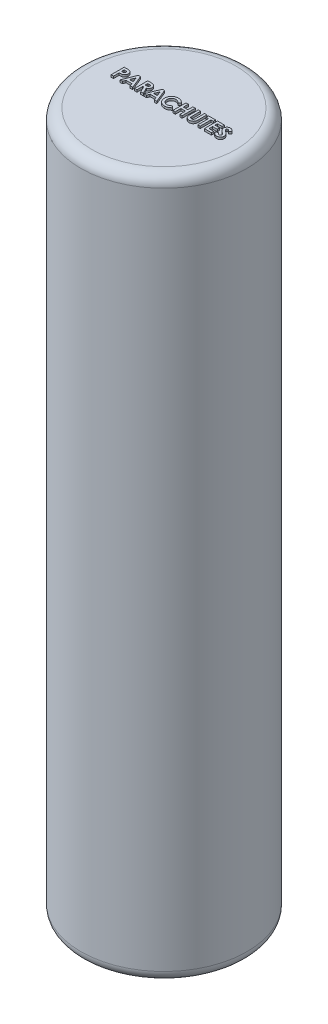
SolidWorks part; units mm, degrees
ref_plane "Front Plane" through (0, 0, 0) normal (0, 0, 1) x (1, 0, 0)
ref_plane "Top Plane" through (0, 0, 0) normal (0, 1, 0) x (1, 0, 0)
ref_plane "Right Plane" through (0, 0, 0) normal (1, 0, 0) x (0, 0, -1)
sketch "Sketch1" plane through (0, 0, 0) normal (0, 1, 0) x (1, 0, 0)
  circle A0 centre (0, 0) radius 48.26
  dimension "D1" = 96.52
extrude "Boss-Extrude1" add sketch "Sketch1" along normal blind 406.4
fillet "Fillet1" radius 6.35 2 edges at (0, 0, 48.26) (0, 406.4, 48.26)
sketch "Sketch2" plane through (0, 406.4, 0) normal (0, 1, 0) x (1, 0, 0)
  line L0 (35.8256, 0) -> (-35.8256, 0) construction
  text T0 "<b>PARACHUTES</b>" font "Century Gothic" height 7.62
  point P4 (0, 0)
extrude "Boss-Extrude2" add sketch "Sketch2" along normal blind 1.27
sketch "Sketch3" plane through (0, 0, 0) normal (0, 0, 1) x (1, 0, 0)
  line L0 (0, 0) -> (0, 396.4867) construction
  text T0 "<b>PARACHUTES</b>" font "Century Gothic" height 20.32
extrude "Cut-Extrude1" cut sketch "Sketch3" against normal mid plane 1.27
